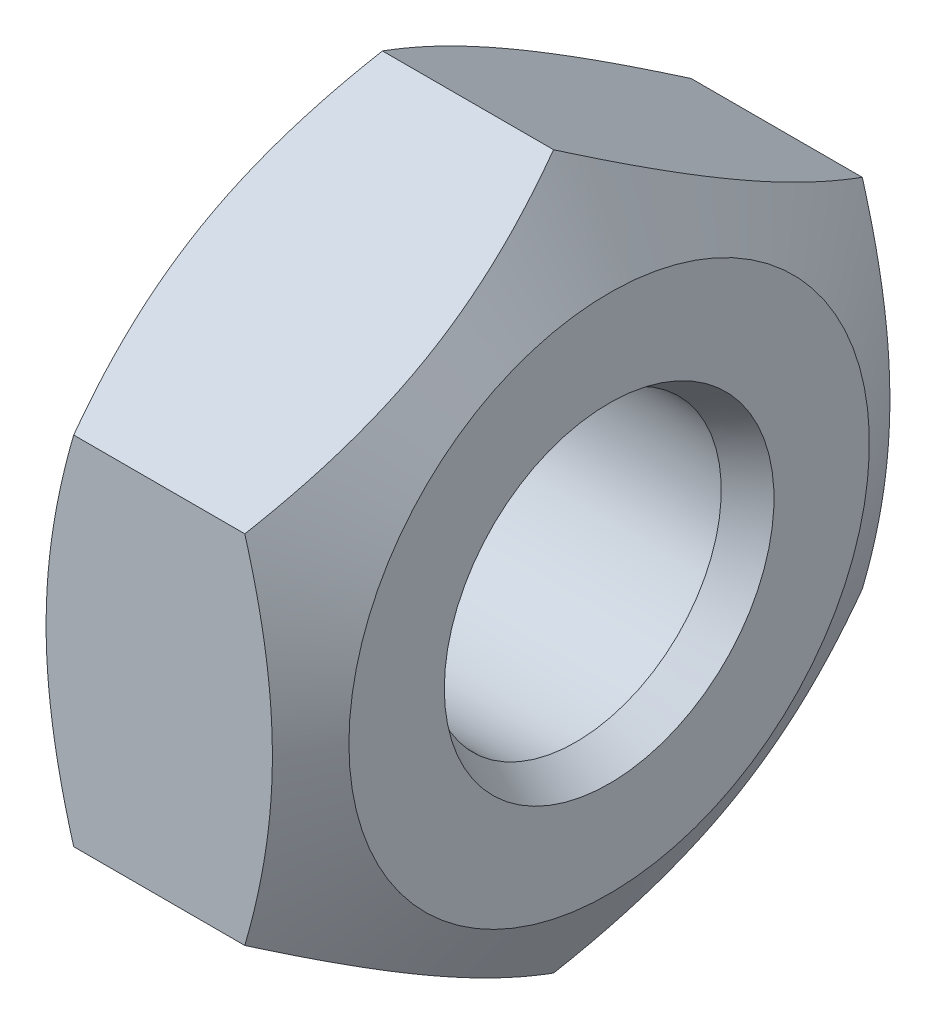
SolidWorks part; units mm, degrees
material "Steel"
ref_plane "Front Plane" through (0, 0, 0) normal (0, 0, 1) x (1, 0, 0)
ref_plane "Top Plane" through (0, 0, 0) normal (0, 1, 0) x (1, 0, 0)
ref_plane "Right Plane" through (0, 0, 0) normal (1, 0, 0) x (0, 0, -1)
ref_plane "Plane1"
sketch "Sketch1" plane through (0, 0, 0) normal (1, 0, 0) x (0, 1, 0)
  line L0 (-4.0415, 0) -> (-2.0207, 3.5)
  line L1 (-2.0207, 3.5) -> (2.0207, 3.5)
  line L2 (2.0207, 3.5) -> (4.0415, 0)
  line L3 (4.0415, 0) -> (2.0207, -3.5)
  line L4 (2.0207, -3.5) -> (-2.0207, -3.5)
  line L5 (-2.0207, -3.5) -> (-4.0415, 0)
  dimension "D1" = 8.0829
extrude "Body" add sketch "Sketch1" along normal blind 3.2
ref_plane "Plane2"
sketch "Sketch2" plane through (0, 0, 0) normal (0, 0, 1) x (1, 0, 0)
  line L0 (0, 4.0415) -> (0, 2.95)
  line L1 (0, 2.95) -> (0.6302, 4.0415)
  line L2 (0.6302, 4.0415) -> (0, 4.0415)
  line L3 (-0.64, 0) -> (3.84, 0) construction
  line L4 (2.5698, 4.0415) -> (3.2, 2.95)
  line L5 (3.2, 2.95) -> (3.2, 4.0415)
  line L6 (3.2, 4.0415) -> (2.5698, 4.0415)
  dimension "D1" = 30
  dimension "D2" = 1.2603
  dimension "D3" = 90
  dimension "D4" = 120
revolve "Chamfer1" cut sketch "Sketch2" angle 360 about L3
hole_wizard "Thread" positions "Sketch4" profile "Sketch3" tap size "M4x0.7" standard "Ansi Metric" end condition through all
sketch "Sketch4" plane through (3.2, 0, 0) normal (1, 0, 0) x (0, 0, -1)
  point P1 (0, 0)
sketch "Sketch3" plane through (3.2, 0, 0) normal (0, 1, 0) x (0, 0, -1)
  line L0 (0, 0) -> (0, 3.2)
  line L1 (0, 3.2) -> (1.65, 3.2)
  line L2 (1.65, 3.2) -> (1.65, 0)
  line L5 (1.65, 0) -> (0, 0)
  line L11 (0, -6.35) -> (0, 107.95) construction
  dimension "Thru Tap Drill Dia." = 3.3
  dimension "Thru Tap Drill Depth" = 3.2
cosmetic thread "Hole Thread1" parameters "D2"=4
chamfer "Chamfer3" distance 0.3789 angle 30 2 edges at (0, 0, -1.65) (3.2, 0, -1.65)
